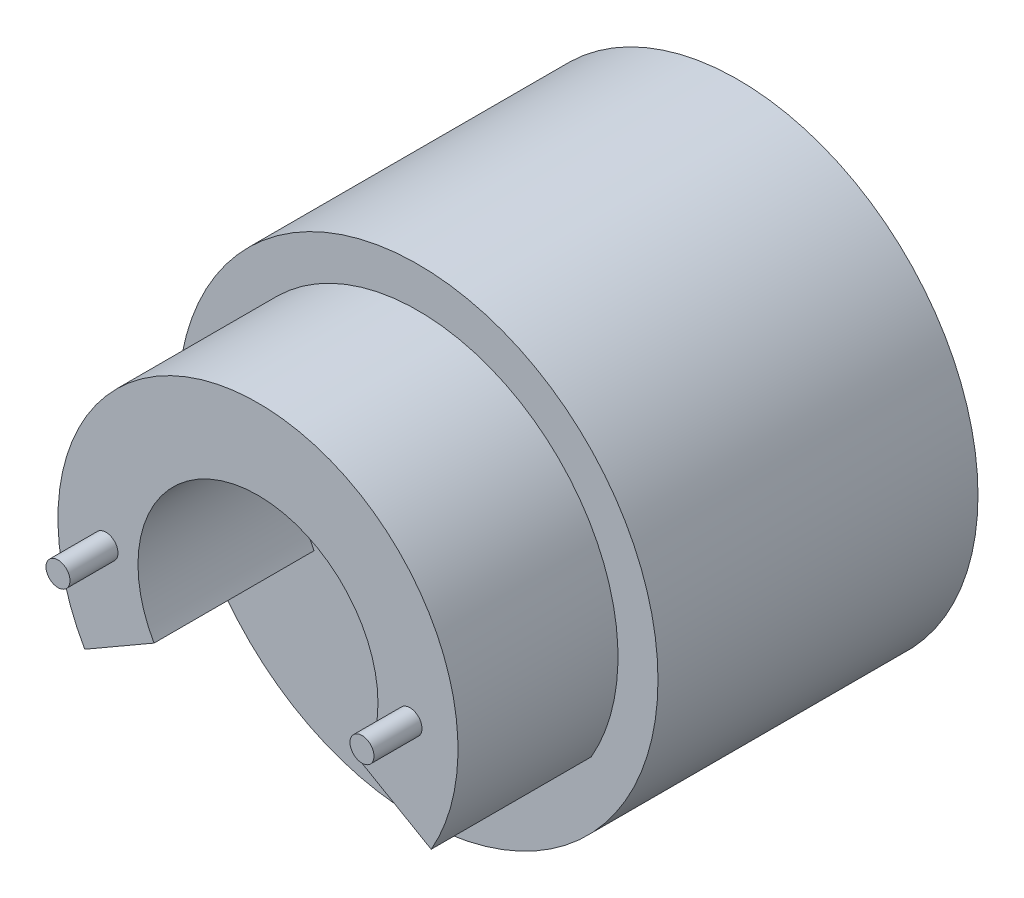
SolidWorks part; units mm, degrees
ref_plane "Front Plane" through (0, 0, 0) normal (0, 0, 1) x (1, 0, 0)
ref_plane "Top Plane" through (0, 0, 0) normal (0, 1, 0) x (1, 0, 0)
ref_plane "Right Plane" through (0, 0, 0) normal (1, 0, 0) x (0, 0, -1)
sketch "Sketch1" plane through (0, 0, 0) normal (0, 0, 1) x (1, 0, 0)
  circle A1 centre (0, 0) radius 15
  dimension "D1" = 30
extrude "Boss-Extrude1" add sketch "Sketch1" along normal blind 20
sketch "Sketch2" plane through (0, 0, 20) normal (0, 0, 1) x (1, 0, 0)
  line L0 (-12.5, 0) -> (12.5, 0) construction
  line L1 (-6.4952, -3.75) -> (-10.8253, -6.25)
  line L2 (6.4952, -3.75) -> (10.8253, -6.25)
  line L3 (-9.5, 0) -> (9.5, 0) construction
  arc A0 (6.4952, -3.75) -> (-6.4952, -3.75) centre (0, 0) ccw
  arc A1 (10.8253, -6.25) -> (-10.8253, -6.25) centre (0, 0) ccw
  circle A2 centre (0, 0) radius 12.5 construction
  circle A3 centre (0, 0) radius 7.5 construction
  point P8 (0, 0)
  point P15 (0, 0)
  dimension "D1" = 15
  dimension "D3" = 30
  dimension "D4" = 30
  dimension "D5" = 19
  dimension "D2" = 5
extrude "Boss-Extrude2" add sketch "Sketch2" along normal blind 10
sketch "Sketch3" plane through (0, 0, 30) normal (0, 0, 1) x (1, 0, 0)
  line L0 (-9.5, 0) -> (9.5, 0) construction
  circle A0 centre (9.5, 0) radius 0.75
  circle A1 centre (-9.5, 0) radius 0.75
  point P4 (0, 0)
  dimension "D2" = 1.5
  dimension "D1" = 19
extrude "Boss-Extrude3" add sketch "Sketch3" along normal blind 3
